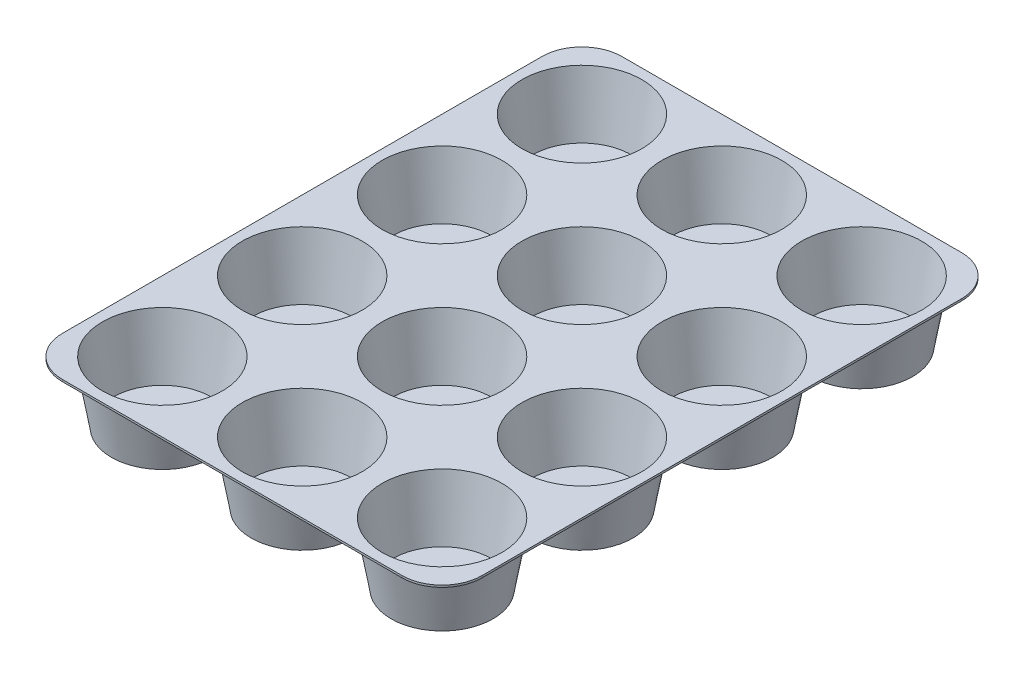
SolidWorks part; units mm, degrees
ref_plane "Front Plane" through (0, 0, 0) normal (0, 0, 1) x (1, 0, 0)
ref_plane "Top Plane" through (0, 0, 0) normal (0, 1, 0) x (1, 0, 0)
ref_plane "Right Plane" through (0, 0, 0) normal (1, 0, 0) x (0, 0, -1)
sketch "Sketch1" plane through (0, 0, 0) normal (0, 1, 0) x (1, 0, 0)
  line L1 (-133.35, 177.8) -> (133.35, 177.8)
  line L2 (-133.35, 177.8) -> (-133.35, -177.8)
  line L3 (-133.35, -177.8) -> (133.35, -177.8)
  line L4 (133.35, 177.8) -> (133.35, -177.8)
  line L5 (-133.35, 177.8) -> (133.35, -177.8) construction
  line L6 (-133.35, -177.8) -> (133.35, 177.8) construction
  point P0 (0, 0)
  dimension "D1" = 355.6
  dimension "D2" = 266.7
extrude "Boss-Extrude1" add sketch "Sketch1" along normal blind 1.27
sketch "Sketch2" plane through (0, 1.27, 0) normal (0, 1, 0) x (1, 0, 0)
  line L0 (-133.35, 177.8) -> (-133.35, -177.8) construction
  line L1 (133.35, 177.8) -> (-133.35, 177.8) construction
  circle A0 centre (-88.9, 133.35) radius 39.37
  point P2 (-83.4921, 131.1345)
  dimension "D1" = 78.74
  dimension "D2" = 44.45
  dimension "D3" = 44.45
extrude "Boss-Extrude2" add sketch "Sketch2" against normal blind 39.37 draft 10
sketch "Sketch3" plane through (0, 1.27, 0) normal (0, 1, 0) x (1, 0, 0)
  line L0 (133.35, 177.8) -> (-133.35, 177.8) construction
  line L1 (-133.35, 177.8) -> (-133.35, -177.8) construction
  circle A0 centre (-88.9, 133.35) radius 38.1
  point P2 (-85.379, 128.3043)
  point P5 (0, 0)
  point P7 (-104.719, 124.0589)
  point P9 (0, 0)
  dimension "D1" = 76.2
  dimension "D2" = 44.45
  dimension "D3" = 44.45
extrude "Cut-Extrude1" cut sketch "Sketch3" against normal blind 38.1 draft 10
pattern_linear "LPattern1" count 3 spacing 88.9 along (1, 0, 0) count 4 spacing 88.9 along (0, 0, 1) of "Boss-Extrude2", "Cut-Extrude1"
fillet "Fillet1" radius 25.4 4 edges at (133.35, 0.635, 177.8) (-133.35, 0.635, 177.8) (133.35, 0.635, -177.8) (-133.35, 0.635, -177.8)
